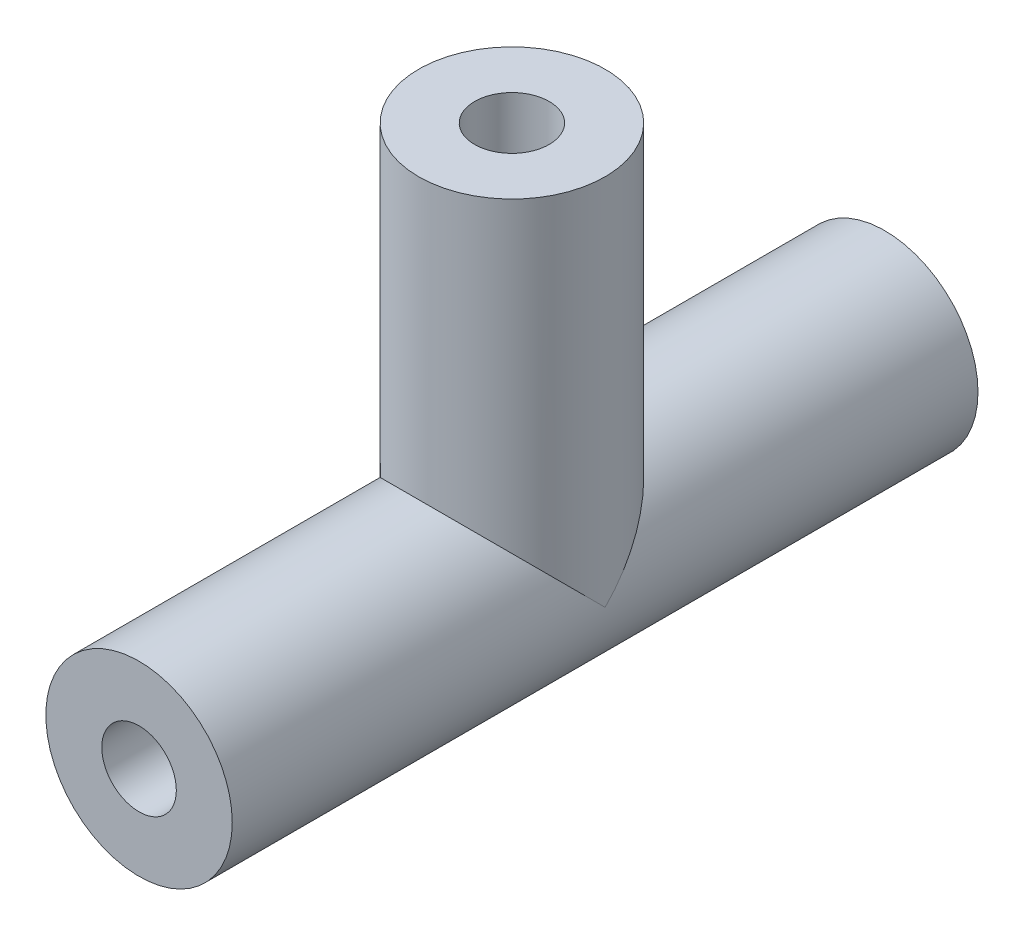
SolidWorks part; units mm, degrees
ref_plane "前视基准面" through (0, 0, 0) normal (0, 0, 1) x (1, 0, 0)
ref_plane "上视基准面" through (0, 0, 0) normal (0, 1, 0) x (1, 0, 0)
ref_plane "右视基准面" through (0, 0, 0) normal (1, 0, 0) x (0, 0, -1)
sketch "草图1" plane through (0, 0, 0) normal (0, 0, 1) x (1, 0, 0)
  circle A0 centre (0, 0) radius 2.5
extrude "凸台-拉伸1" add sketch "草图1" along normal blind 15 and the other way blind 5
ref_plane "基准面1" through (0, 10, 0) normal (0, 1, 0) x (1, 0, 0)
sketch "草图3" plane through (0, 10, 0) normal (0, 1, 0) x (1, 0, 0)
  circle A0 centre (0, -5) radius 2.5
extrude "凸台-拉伸2" add sketch "草图3" against normal up to surface (7.5 mm away)
sketch "草图6" plane through (0, 0, -5) normal (0, 0, -1) x (-1, 0, 0)
  circle A0 centre (0, 0) radius 1
extrude "切除-拉伸1" cut sketch "草图6" against normal up to next
sketch "草图7" plane through (0, 10, 0) normal (0, 1, 0) x (1, 0, 0)
  circle A0 centre (0, -5) radius 1
extrude "切除-拉伸3" cut sketch "草图7" against normal up to surface (9 mm away) contours A0
